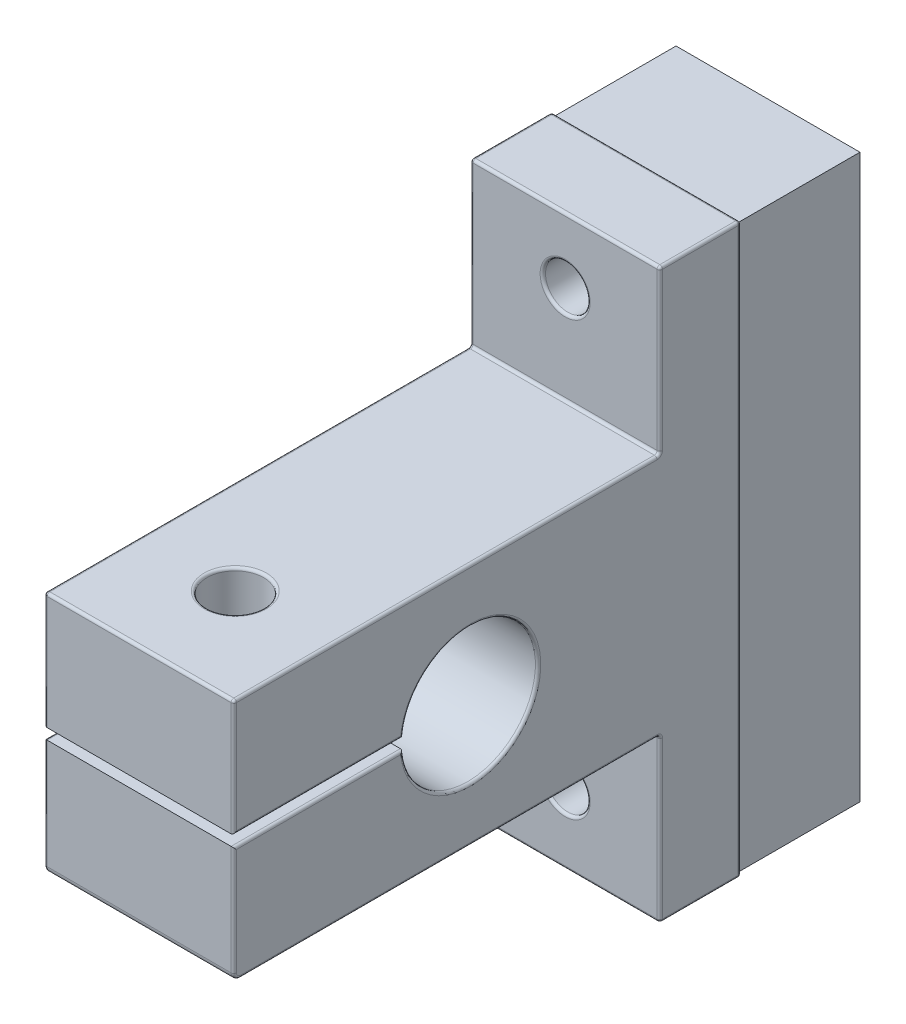
SolidWorks part; units mm, degrees
ref_plane "Front Plane" through (0, 0, 0) normal (0, 0, 1) x (1, 0, 0)
ref_plane "Top Plane" through (0, 0, 0) normal (0, 1, 0) x (1, 0, 0)
ref_plane "Right Plane" through (0, 0, 0) normal (1, 0, 0) x (0, 0, -1)
ref_plane "Plane1" through (7, 0, 0) normal (1, 0, 0) x (0, 0, -1)
sketch "Sketch1" plane through (7, 0, 0) normal (1, 0, 0) x (0, 0, -1)
  line L0 (47.5933, 63.1942) -> (10.0933, 63.1942)
  line L1 (10.0933, 63.1942) -> (10.0933, 21.1942)
  line L2 (10.0933, 21.1942) -> (47.5933, 21.1942)
  line L3 (47.5933, 21.1942) -> (47.5933, 63.1942)
extrude "Boss-Extrude1" add sketch "Sketch1" against normal blind 14
sketch "Sketch2" plane through (-7, 0, 0) normal (-1, 0, 0) x (0, 0, 1)
  line L0 (-10.0933, 21.1942) -> (-10.0933, 33.1942)
  line L1 (-10.0933, 33.1942) -> (-41.5933, 33.1942)
  line L2 (-41.5933, 33.1942) -> (-41.5933, 21.1942)
  line L3 (-41.5933, 21.1942) -> (-10.0933, 21.1942)
extrude "Cut-Extrude1" cut sketch "Sketch2" against normal through all
sketch "Sketch3" plane through (-7, 0, 0) normal (-1, 0, 0) x (0, 0, 1)
  line L0 (-10.0933, 63.1942) -> (-41.5933, 63.1942)
  line L1 (-41.5933, 63.1942) -> (-41.5933, 51.1942)
  line L2 (-41.5933, 51.1942) -> (-10.0933, 51.1942)
  line L3 (-10.0933, 51.1942) -> (-10.0933, 63.1942)
extrude "Cut-Extrude2" cut sketch "Sketch3" against normal through all
sketch "Sketch4" plane through (-7, 0, 0) normal (-1, 0, 0) x (0, 0, 1)
  line L0 (-10.0933, 41.7942) -> (-10.0933, 42.5942)
  line L1 (-10.0933, 42.5942) -> (-22.6093, 42.5942)
  line L2 (-22.6093, 41.7942) -> (-10.0933, 41.7942)
  arc A0 (-22.6093, 42.5942) -> (-22.6093, 41.7942) centre (-27.5933, 42.1942) cw
extrude "Cut-Extrude3" cut sketch "Sketch4" against normal through all
ref_plane "Plane2" through (0, 0, -27.5933) normal (0, 0, 1) x (1, 0, 0)
sketch "Sketch5" plane through (0, 0, -27.5933) normal (0, 0, 1) x (1, 0, 0)
  line L0 (-7, 47.1942) -> (-7, 42.1942)
  line L1 (-7, 42.1942) -> (7, 42.1942)
  line L2 (7, 42.1942) -> (7, 47.1942)
  line L3 (7, 47.1942) -> (-7, 47.1942)
  line L4 (-7, 42.1942) -> (7, 42.1942) construction
revolve "Cut-Revolve1" cut sketch "Sketch5" angle 360 about L4
hole_wizard "Ø4.2 (4.2) Diameter Hole1" positions "Sketch7" profile "Sketch6" hole size "Ø4.2" standard "ANSI Metric"
sketch "Sketch7" plane through (0, 42.5942, 0) normal (0, -1, 0) x (-1, 0, 0)
  point P0 (0, 17.2029)
sketch "Sketch6" plane through (0, 42.5942, -17.2029) normal (1, 0, 0) x (0, 0, -1)
  line L0 (0, 0) -> (0, 20.6)
  line L1 (0, 20.6) -> (2.1, 20.6)
  line L2 (2.1, 20.6) -> (2.1, 0)
  line L5 (2.1, 0) -> (0, 0)
  line L11 (0, -6.35) -> (0, 107.95) construction
  dimension "Thru Hole Dia." = 4.2
  dimension "Thru Hole Depth" = 20.6
hole_wizard "Ø3.3 (3.3) Diameter Hole1" positions "Sketch9" profile "Sketch8" hole size "Ø3.3" standard "ANSI Metric"
sketch "Sketch9" plane through (0, 0, -47.5933) normal (0, 0, -1) x (-1, 0, 0)
  point P0 (0, 26.3942)
sketch "Sketch8" plane through (0, 26.3942, -47.5933) normal (1, 0, 0) x (0, 1, 0)
  line L0 (0, 0) -> (0, 37.5)
  line L1 (0, 37.5) -> (1.65, 37.5)
  line L2 (1.65, 37.5) -> (1.65, 0)
  line L5 (1.65, 0) -> (0, 0)
  line L11 (0, -6.35) -> (0, 107.95) construction
  dimension "Thru Hole Dia." = 3.3
  dimension "Thru Hole Depth" = 37.5
hole_wizard "Ø3.3 (3.3) Diameter Hole2" positions "Sketch11" profile "Sketch10" hole size "Ø3.3" standard "ANSI Metric"
sketch "Sketch11" plane through (0, 0, -41.5933) normal (0, 0, 1) x (1, 0, 0)
  point P0 (0, 58.3942)
sketch "Sketch10" plane through (0, 58.3942, -41.5933) normal (1, 0, 0) x (0, -1, 0)
  line L0 (0, 0) -> (0, 6)
  line L1 (0, 6) -> (1.65, 6)
  line L2 (1.65, 6) -> (1.65, 0)
  line L5 (1.65, 0) -> (0, 0)
  line L11 (0, -6.35) -> (0, 107.95) construction
  dimension "Thru Hole Dia." = 3.3
  dimension "Thru Hole Depth" = 6
fillet "Fillet1" radius 0.5 1 edges at (0, 33.1942, -10.0933)
fillet "Fillet2" radius 0.2 39 edges at (7, 46.8942, -10.0933) (0, 51.1942, -10.0933) (7, 42.5942, -16.3513) (7, 51.1942, -25.8433) (7, 57.1942, -41.5933) (-7, 46.8942, -10.0933) (0, 63.1942, -41.5933) (-7, 57.1942, -41.5933) (-7, 51.1942, -25.8433) (7, 42.1942, -32.5933) (7, 63.1942, -44.5933) (-7, 42.5942, -16.3513) (0, 63.1942, -47.5933) (-7, 63.1942, -44.5933) (7, 41.7942, -16.3513) (7, 42.1942, -47.5933) (-7, 42.1942, -32.5933) (0, 21.1942, -47.5933) (-7, 42.1942, -47.5933) (7, 27.1942, -41.5933) (7, 33.1942, -26.0933) (7, 33.3406, -10.2397) (7, 37.7442, -10.0933) (7, 21.1942, -44.5933) (-7, 41.7942, -16.3513) (-7, 21.1942, -44.5933) (0, 21.1942, -41.5933) (-7, 37.7442, -10.0933) (-7, 33.3406, -10.2397) (-7, 33.1942, -26.0933) (-7, 27.1942, -41.5933) (0, 28.0442, -41.5933) (0, 33.1942, -41.5933) (1.65, 58.3942, -47.5933) (0, 51.1942, -19.3029) (0, 51.1942, -41.5933) (0, 28.0442, -47.5933) (1.65, 58.3942, -41.5933) (0, 42.5942, -19.3029)
sketch "Sketch12" plane through (0, 0, -47.5933) normal (0, 0, -1) x (-1, 0, 0)
  line L4 (6.8, 21.3942) -> (6.8, 62.9942)
  line L5 (6.8, 62.9942) -> (-6.8, 62.9942)
  line L6 (-6.8, 62.9942) -> (-6.8, 21.3942)
  line L7 (-6.8, 21.3942) -> (6.8, 21.3942)
  line L8 (6.8, 21.3942) -> (6.8, 62.9942)
  line L9 (6.8, 62.9942) -> (-6.8, 62.9942)
  line L10 (-6.8, 62.9942) -> (-6.8, 21.3942)
  line L11 (-6.8, 21.3942) -> (6.8, 21.3942)
  circle A0 centre (0, 26.3942) radius 1.65 construction
  circle A1 centre (0, 26.3942) radius 1.65
  circle A2 centre (0, 58.3942) radius 1.65 construction
  circle A3 centre (0, 58.3942) radius 1.65
  dimension "D1" = 0
extrude "Boss-Extrude2" add sketch "Sketch12" along normal blind 9
